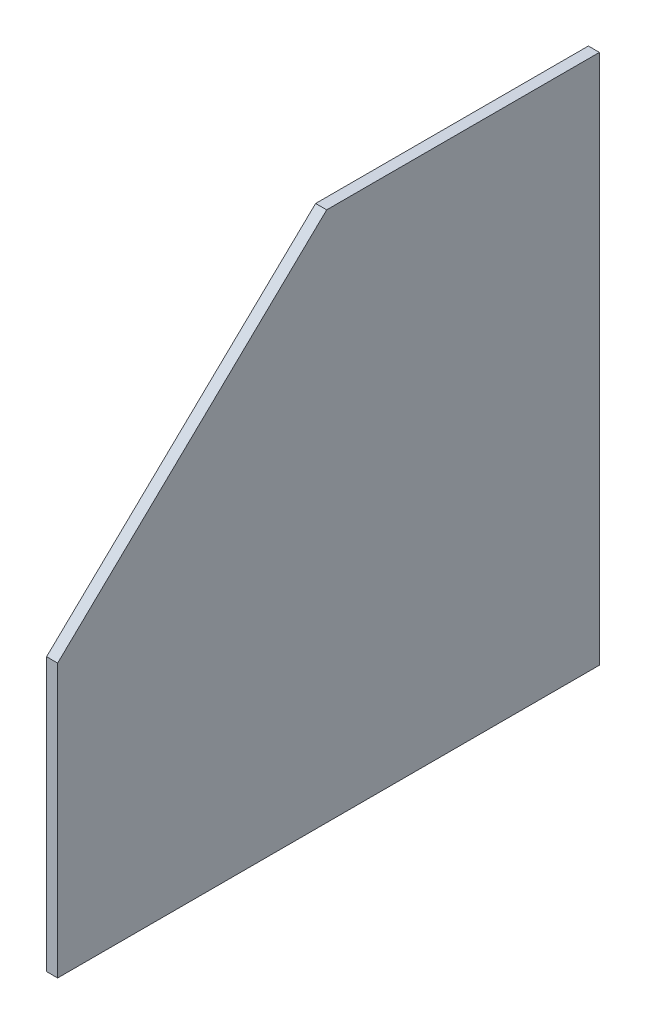
SolidWorks part; units mm, degrees
material "Oak"
ref_plane "Front" through (0, 0, 0) normal (0, 0, 1) x (1, 0, 0)
ref_plane "Top" through (0, 0, 0) normal (0, 1, 0) x (1, 0, 0)
ref_plane "Right" through (0, 0, 0) normal (1, 0, 0) x (0, 0, -1)
sketch "Sketch2" plane through (0, 0, 0) normal (-1, 0, 0) x (0, 0, 1)
  line L0 (0, 0) -> (-933.45, 0)
  line L1 (-933.45, 0) -> (-933.45, 914.4)
  line L2 (-933.45, 914.4) -> (-463.55, 914.4)
  line L3 (-463.55, 914.4) -> (0, 469.9)
  line L4 (0, 469.9) -> (0, 0)
  dimension "D1" = 469.9
extrude "Boss-Extrude1" add sketch "Sketch2" along normal blind 19.05
equation "\"D1@Boss-Extrude1\"=\"MAT_THICKNESS@shapeoko_enclosure.sldasm\""
